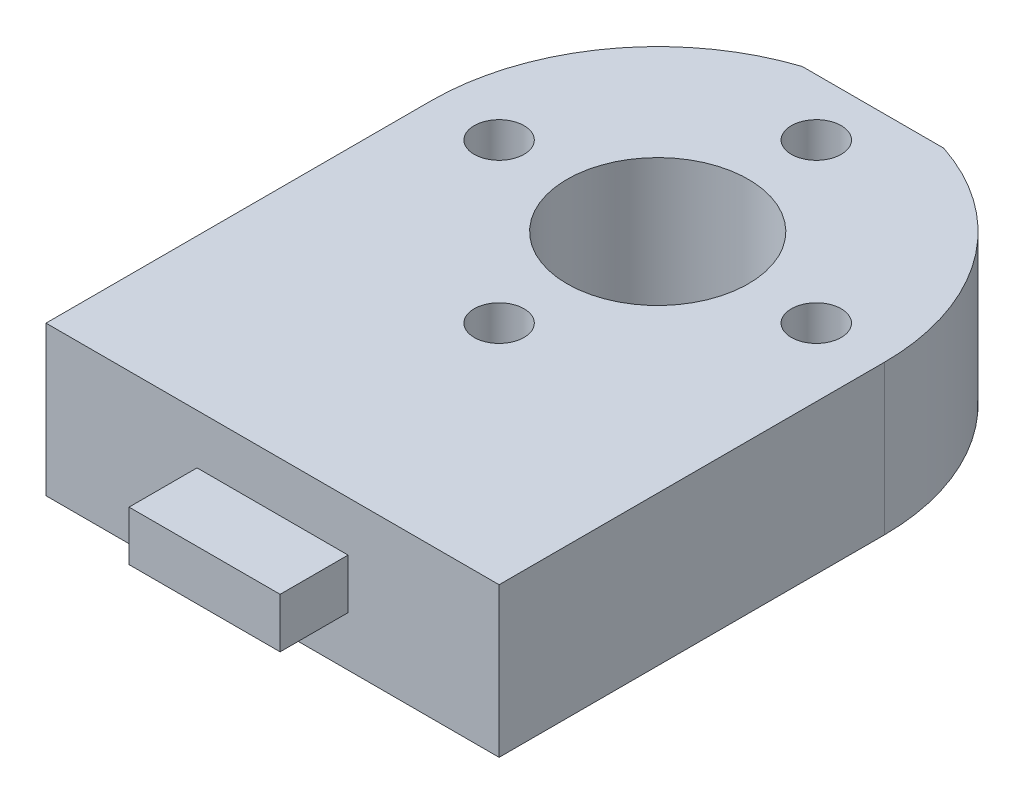
SolidWorks part; units mm, degrees
material "PF"
ref_plane "前视基准面" through (0, 0, 0) normal (0, 0, 1) x (1, 0, 0)
ref_plane "上视基准面" through (0, 0, 0) normal (0, 1, 0) x (1, 0, 0)
ref_plane "右视基准面" through (0, 0, 0) normal (1, 0, 0) x (0, 0, -1)
sketch "草图1" plane through (0, 0, 0) normal (0, 1, 0) x (1, 0, 0)
  line L0 (-10, -17) -> (10, -17)
  line L1 (-10, -17) -> (-10, 0)
  line L2 (10, -17) -> (10, 0)
  line L3 (-3.1225, 9.5) -> (3.1225, 9.5)
  line L4 (0, -17) -> (0, 0) construction
  line L5 (0, 0) -> (2.8284, 2.8284) construction
  line L6 (0, 0) -> (-7, 0) construction
  line L7 (-10, 0) -> (10, 0) construction
  circle A4 centre (0, 0) radius 4
  circle A5 centre (-7, 0) radius 1.1
  circle A6 centre (0, 7) radius 1.1
  circle A7 centre (7, 0) radius 1.1
  circle A8 centre (0, -7) radius 1.1
  arc A9 (10, 0) -> (3.1225, 9.5) centre (0, 0) ccw
  arc A10 (-3.1225, 9.5) -> (-10, 0) centre (0, 0) ccw
  point P1 (0, 0)
  dimension "D4" = 4
  dimension "D3" = 7
extrude "凸台-拉伸2" add sketch "草图1" along normal blind 6.6
sketch "草图2" plane through (0, 0, 17) normal (0, 0, 1) x (1, 0, 0)
  line L0 (3.3333, 2.2) -> (-3.3333, 2.2)
  line L1 (3.3333, 2.2) -> (3.3333, 4.4)
  line L2 (-3.3333, 2.2) -> (-3.3333, 4.4)
  line L3 (3.3333, 4.4) -> (-3.3333, 4.4)
  line L4 (3.3333, 3.3) -> (10, 3.3) construction
  line L5 (10, 6.6) -> (10, 0) construction
  line L6 (-3.3333, 3.3) -> (-10, 3.3)
  line L7 (-10, 6.6) -> (-10, 0) construction
  line L8 (2.3364, 0) -> (2.3364, 2.2)
  line L9 (-10, 0) -> (10, 0) construction
  line L10 (2.8791, 4.4) -> (2.8791, 6.6)
  line L11 (-10, 6.6) -> (10, 6.6) construction
extrude "凸台-拉伸3" add sketch "草图2" along normal blind 3 contours L1 L3 L2 L0
